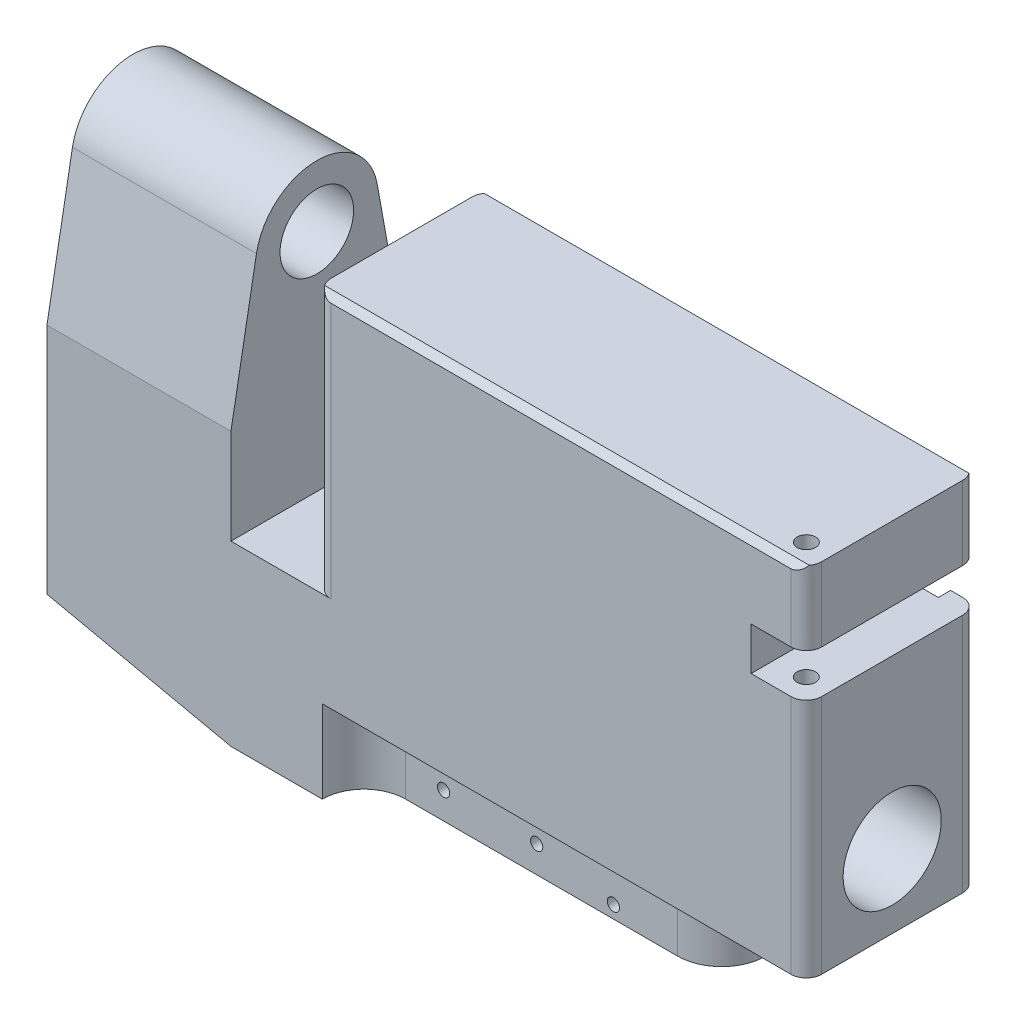
SolidWorks part; units mm, degrees
material "7050-T7651"
ref_plane "前视基准面" through (0, 0, 0) normal (0, 0, 1) x (1, 0, 0)
ref_plane "上视基准面" through (0, 0, 0) normal (0, 1, 0) x (1, 0, 0)
ref_plane "右视基准面" through (0, 0, 0) normal (1, 0, 0) x (0, 0, -1)
sketch "Sketch1" plane through (0, 0, 0) normal (0, 0, 1) x (1, 0, 0)
  line L0 (0, 0) -> (0, 46.74)
  line L1 (0, 46.74) -> (-30, 46.74)
  line L2 (-30, 46.74) -> (-30, -22.49)
  line L3 (-30, -22.49) -> (0, -28.98)
  line L4 (0, -28.98) -> (73.21, -28.98)
  line L5 (73.21, -28.98) -> (73.21, -15.51)
  line L6 (73.21, -15.51) -> (93.8, -15.51)
  line L7 (93.8, -15.51) -> (93.8, 23.71)
  line L8 (93.8, 23.71) -> (84.8, 23.71)
  line L9 (84.8, 23.71) -> (84.8, 30.71)
  line L10 (84.8, 30.71) -> (93.8, 30.71)
  line L11 (93.8, 30.71) -> (93.8, 42.75)
  line L12 (93.8, 42.75) -> (13.8, 42.75)
  line L13 (13.8, 42.75) -> (13.8, 0)
  line L14 (13.8, 0) -> (0, 0)
  circle A0 centre (55.55, -17.96) radius 1
  circle A1 centre (55.55, -26.93) radius 1
  circle A2 centre (43.04, -24.61) radius 1
  circle A3 centre (27.87, -24.61) radius 1
  dimension "D13" = 17.66
  dimension "D16" = 2
  dimension "D17" = 2
  dimension "D21" = 2
  dimension "D22" = 2
  dimension "D1" = 30
  dimension "D2" = 13.8
  dimension "D3" = 80
  dimension "D4" = 9
  dimension "D5" = 13.47
  dimension "D6" = 20.59
  dimension "D7" = 6.49
  dimension "D8" = 42.75
  dimension "D9" = 7
  dimension "D10" = 3.99
  dimension "D11" = 12.04
  dimension "D12" = 39.22
  dimension "D14" = 8.97
  dimension "D15" = 41.67
  dimension "D18" = 12.51
  dimension "D19" = 15.17
  dimension "D20" = 48.32
extrude "Extrude1" add sketch "Sketch1" along normal mid plane 28
chamfer "Chamfer1" distance 1 angle 45 2 edges at (53.8, 42.75, -14) (53.8, 42.75, 14)
fillet "Fillet1" radius 2.5 6 edges at (13.8, 20.875, -14) (93.8, 4.1, -14) (93.8, 36.23, -14) (93.8, 36.23, 14) (93.8, 4.1, 14) (13.8, 20.875, 14)
sketch "Sketch2" plane through (-30, 0, 0) normal (-1, 0, 0) x (0, 0, 1)
  line L0 (14, 46.74) -> (-14, 46.74) construction
  line L1 (-9.8404, 38.5197) -> (-14, 15.52)
  line L2 (-14, 46.74) -> (-14, -22.49) construction
  line L3 (0, 40.9581) -> (0, 6.2186) construction
  line L4 (9.8404, 38.5197) -> (14, 15.52)
  line L5 (-14, 15.52) -> (-14, 50.2525)
  line L6 (-14, 50.2525) -> (14, 50.2525)
  line L7 (14, 50.2525) -> (14, 15.52)
  arc A0 (9.8404, 38.5197) -> (-9.8404, 38.5197) centre (0, 36.74) ccw
  dimension "D1" = 31.22
  dimension "D2" = 10
extrude "Extrude4" cut sketch "Sketch2" against normal up to surface (30 mm away) up to face at (0, 23.37, 0)
sketch "Sketch3" plane through (0, 0, 0) normal (0, 0, 1) x (1, 0, 0)
  line L0 (85.68, 36.73) -> (-30, 36.73) construction
  line L1 (-30, 38.5197) -> (-30, 15.52) construction
  line L2 (-30, 36.73) -> (-30, 44.28)
  line L3 (-30, 46.74) -> (-30, 38.5197) construction
  line L4 (-30, 44.28) -> (-18.3, 44.28)
  line L5 (-18.3, 44.28) -> (-18.3, 42.73)
  line L6 (-18.3, 42.73) -> (0, 42.73)
  line L7 (0, 38.5197) -> (0, 46.74) construction
  line L8 (85.68, 36.73) -> (85.68, 41.245)
  line L9 (85.68, 41.245) -> (13.8, 41.245)
  line L10 (13.8, 0) -> (13.8, 42.75) construction
  line L11 (85.68, 36.73) -> (-30, 36.73)
  line L12 (0, 42.73) -> (0, 41.245)
  line L13 (13.8, 41.245) -> (0, 41.245)
  dimension "D1" = 9.03
  dimension "D2" = 12
  dimension "D3" = 15.1
  dimension "D4" = 11.7
  dimension "D5" = 71.88
  dimension "D6" = 59.22
revolve "Cut-Revolve1" cut sketch "Sketch3" angle 360 about L0
cosmetic thread "Cosmetic Thread1" parameters "D2"=16
sketch "Sketch4" plane through (0, 0, 0) normal (0, 0, 1) x (1, 0, 0)
  line L0 (-36.1569, -3.49) -> (100.5345, -3.49) construction
  line L2 (-32.9547, 6.51) -> (-32.9547, -3.49)
  line L4 (-32.9547, 6.51) -> (-1.1177, 6.51)
  line L5 (-1.1177, 6.51) -> (-1.1177, -0.99)
  line L6 (-1.1177, -0.99) -> (21.6, -0.99)
  line L7 (21.6, -0.99) -> (21.6, 4.51)
  line L8 (21.6, 4.51) -> (100.5345, 4.51)
  line L10 (100.5345, -3.49) -> (-32.9547, -3.49)
  line L13 (100.5345, 4.51) -> (100.5345, -3.49)
  dimension "D1" = 19
  dimension "D2" = 16
  dimension "D3" = 20
  dimension "D4" = 5
sketch "Sketch5" plane through (0, 42.75, 0) normal (0, 1, 0) x (1, 0, 0)
  line L0 (93.8, -11.5) -> (93.8, 11.5) construction
  line L2 (91.3, -14) -> (16.3, -14) construction
  circle A0 centre (89.8, -10) radius 1.5
  dimension "D1" = 4
  dimension "D3" = 3
  dimension "D2" = 4
extrude "Extrude5" cut sketch "Sketch5" against normal blind 23
sketch "Sketch6" plane through (0, 0, 0) normal (0, 1, 0) x (1, 0, 0)
  line L0 (93.8, -11.5) -> (93.8, 11.5) construction
  circle A0 centre (-13.6, 0) radius 2.55
  circle A1 centre (-24.9, 0) radius 2.05
  dimension "D1" = 107.4
  dimension "D3" = 5.1
  dimension "D4" = 4.1
  dimension "D2" = 118.7
extrude "Extrude6" cut sketch "Sketch6" against normal through all
cosmetic thread "Cosmetic Thread3" parameters "D2"=6
cosmetic thread "Cosmetic Thread4" parameters "D2"=5
sketch "Sketch7" plane through (0, -28.98, 0) normal (0, -1, 0) x (1, 0, 0)
  line L0 (-3.6205, 0) -> (80.3195, 0) construction
  line L1 (21.69, 7.2) -> (66.01, 7.2)
  line L2 (0, 14) -> (73.21, 14) construction
  line L3 (93.8, 11.5) -> (93.8, -11.5) construction
  line L4 (21.69, -7.2) -> (66.01, -7.2)
  line L5 (14.89, 14) -> (80.3195, 14)
  line L6 (73.21, 14) -> (91.3, 14) construction
  line L7 (80.3195, 14) -> (80.3195, -14)
  line L8 (73.21, -14) -> (91.3, -14) construction
  line L9 (80.3195, -14) -> (14.89, -14)
  arc A0 (66.01, 7.2) -> (66.01, -7.2) centre (66.01, 0) cw
  arc A1 (21.69, 7.2) -> (14.89, 14) centre (21.69, 14) cw
  arc A2 (21.69, -7.2) -> (14.89, -14) centre (21.69, -14) ccw
  dimension "D1" = 27.79
  dimension "D3" = 7.2
  dimension "D4" = 6.8
  dimension "D2" = 72.11
extrude "Extrude7" cut sketch "Sketch7" against normal up to surface (13.47 mm away) up to face at (86.2759, -15.51, 0)
sketch "Sketch8" plane through (0, -28.98, 0) normal (0, -1, 0) x (1, 0, 0)
  line L0 (21.69, 0) -> (66.01, 0) construction
  line L1 (21.69, 5.2) -> (66.01, 5.2)
  line L2 (21.69, -5.2) -> (66.01, -5.2)
  line L3 (93.8, 11.5) -> (93.8, -11.5) construction
  line L4 (21.69, 5.2) -> (21.69, -5.2)
  arc A1 (66.01, -5.2) -> (66.01, 5.2) centre (66.01, 0) ccw
  point P3 (43.85, 0)
  dimension "D1" = 5.2
  dimension "D2" = 27.79
  dimension "D3" = 72.11
  dimension "D4" = 10.4
extrude "Extrude8" cut sketch "Sketch8" against normal blind 15.49
sketch "Sketch9" plane through (0, -28.98, 0) normal (0, -1, 0) x (1, 0, 0)
  line L0 (17.74, 0) -> (21.69, 0) construction
  line L1 (21.69, 5.2) -> (21.69, -5.2) construction
  line L2 (17.74, 5.2) -> (21.69, 5.2)
  line L3 (17.74, -5.2) -> (21.69, -5.2)
  line L4 (93.8, 11.5) -> (93.8, -11.5) construction
  line L5 (11.7354, 5.4066) -> (15.0008, 2.4664) construction
  line L6 (11.7354, 5.4066) -> (17.74, 0) construction
  line L7 (0, 14) -> (14.89, 14) construction
  line L9 (13.2347, 7.0717) -> (15.7521, 4.805)
  line L10 (21.69, 5.2) -> (21.69, -5.2)
  line L11 (10.2361, 3.7414) -> (12.7535, 1.4747)
  arc A0 (12.7535, 1.4747) -> (17.74, -5.2) centre (17.74, 0) ccw
  arc A2 (13.2347, 7.0717) -> (10.2361, 3.7414) centre (11.7354, 5.4066) ccw
  arc A4 (17.74, 5.2) -> (15.7521, 4.805) centre (17.74, 0) ccw
  point P4 (19.715, 0)
  point P11 (13.3681, 3.9365)
  point P13 (13.9795, -3.386)
  dimension "D1" = 2.2407
  dimension "D3" = 5.2
  dimension "D2" = 76.06
  dimension "D4" = 42
extrude "Extrude21" cut sketch "Sketch9" against normal blind 10.11
sketch "Sketch22" plane through (0, -13.49, 0) normal (0, -1, 0) x (1, 0, 0)
  line L0 (93.8, 11.5) -> (93.8, -11.5) construction
  circle A0 centre (17.74, 0) radius 1.2
  dimension "D1" = 76.06
  dimension "D2" = 2.4
extrude "Extrude22" cut sketch "Sketch22" along normal through all
cosmetic thread "Cosmetic Thread11" parameters "D2"=3
sketch "Sketch23" plane through (0, -13.49, 0) normal (0, -1, 0) x (1, 0, 0)
  circle A0 centre (11.7354, 5.4066) radius 1.2
  dimension "D1" = 2.4
extrude "Extrude23" cut sketch "Sketch23" against normal blind 8 and the other way through all
cosmetic thread "Cosmetic Thread12" parameters "D2"=3
sketch "Sketch12" plane through (0, 0, 0) normal (0, 1, 0) x (1, 0, 0)
  line L1 (13.8, -11.5) -> (13.8, 11.5) construction
  line L2 (16.3, 14) -> (0, 14) construction
  circle A0 centre (9.63, 4.53) radius 1.5
  dimension "D1" = 9.47
  dimension "D3" = 3
  dimension "D2" = 4.17
extrude "Extrude12" cut sketch "Sketch12" against normal blind 8.5
sketch "Sketch13" plane through (0, -28.98, 0) normal (0, -1, 0) x (1, 0, 0)
  line L1 (93.8, 11.5) -> (93.8, -11.5) construction
  line L2 (0, -14) -> (14.89, -14) construction
  circle A0 centre (9.63, -4.53) radius 2.5
  dimension "D3" = 5
  dimension "D2" = 84.17
  dimension "9.4" = 9.47
extrude "Extrude13" cut sketch "Sketch13" against normal up to surface (20.48 mm away) up to face at (8.13, -8.5, -4.53)
cosmetic thread "Cosmetic Thread7" parameters "D1"=10, "D2"=6
sketch "Sketch14" plane through (0, 0, 0) normal (0, 1, 0) x (1, 0, 0)
  line L0 (-30, 9.8404) -> (-30, -9.8404) construction
  circle A0 centre (-13.6, 0) radius 2.25
  dimension "D1" = 16.4
  dimension "D2" = 4.5
extrude "Extrude14" cut sketch "Sketch14" along normal up to next
sketch "Sketch15" plane through (0, -13.49, 0) normal (0, -1, 0) x (1, 0, 0)
  line L0 (93.8, 11.5) -> (93.8, -11.5) construction
  line L1 (26.18, 2.5) -> (66.99, 2.5)
  line L2 (26.18, 2.5) -> (26.18, -2.5)
  line L3 (26.18, -2.5) -> (66.99, -2.5)
  line L4 (66.99, 2.5) -> (66.99, -2.5)
  line L5 (26.18, 2.5) -> (66.99, -2.5) construction
  line L6 (26.18, -2.5) -> (66.99, 2.5) construction
  point P0 (46.585, 0)
  dimension "D1" = 26.81
  dimension "D2" = 67.62
  dimension "D3" = 5
extrude "Extrude15" cut sketch "Sketch15" against normal blind 20
sketch "Sketch16" plane through (0, 0, 14) normal (0, 0, 1) x (1, 0, 0)
  line L0 (84.8, 30.71) -> (13.8, 30.71)
  line L1 (13.8, 0) -> (13.8, 42.75) construction
  line L2 (13.8, 30.71) -> (13.8, 6.5)
  line L3 (13.8, 6.5) -> (83.95, 6.5)
  line L4 (84.8, 23.71) -> (82.78, 23.71)
  line L5 (82.78, 23.71) -> (82.78, 19.71)
  line L6 (84.47, 18.02) -> (85.26, 18.02)
  line L7 (87.32, 15.96) -> (87.32, 9.87)
  line L8 (93.8, 23.71) -> (93.8, -15.51) construction
  line L9 (91.3, 23.71) -> (84.8, 23.71) construction
  line L10 (84.8, 30.71) -> (84.8, 23.71)
  arc A0 (87.32, 9.87) -> (83.95, 6.5) centre (83.95, 9.87) cw
  arc A1 (82.78, 19.71) -> (84.47, 18.02) centre (84.47, 19.71) ccw
  arc A2 (85.26, 18.02) -> (87.32, 15.96) centre (85.26, 15.96) cw
  dimension "D3" = 3.37
  dimension "D5" = 8.54
  dimension "D4" = 9.33
  dimension "D1" = 24.21
  dimension "D2" = 11.02
  dimension "D7" = 4
  dimension "D8" = 7.75
sketch "Sketch24" plane through (0, 0, -14) normal (0, 0, -1) x (-1, 0, 0)
  line L0 (-84.8, 30.71) -> (-13.8, 30.71)
  line L1 (-13.8, 30.71) -> (-13.8, 6.5)
  line L2 (-84.8, 30.71) -> (-84.8, 23.71)
  line L3 (-84.8, 23.71) -> (-82.78, 23.71)
  line L4 (-82.78, 23.71) -> (-82.78, 19.71)
  line L5 (-87.32, 15.96) -> (-87.32, 9.87)
  line L8 (-82.78, 23.71) -> (-82.78, 19.71)
  line L9 (-84.8, 23.71) -> (-82.78, 23.71)
  line L10 (-84.8, 30.71) -> (-84.8, 23.71)
  line L11 (-13.8, 30.71) -> (-84.8, 30.71)
  line L12 (-13.8, 6.5) -> (-13.8, 30.71)
  line L13 (-83.95, 6.5) -> (-13.8, 6.5)
  line L14 (-87.32, 15.96) -> (-87.32, 9.87)
  line L15 (-84.47, 18.02) -> (-85.26, 18.02)
  line L21 (-83.95, 6.5) -> (-13.8, 6.5)
  line L23 (-84.47, 18.02) -> (-85.26, 18.02)
  arc A0 (-87.32, 9.87) -> (-83.95, 6.5) centre (-83.95, 9.87) ccw
  arc A1 (-85.26, 18.02) -> (-87.32, 15.96) centre (-85.26, 15.96) ccw
  arc A2 (-82.78, 19.71) -> (-84.47, 18.02) centre (-84.47, 19.71) cw
  arc A3 (-87.32, 9.87) -> (-83.95, 6.5) centre (-83.95, 9.87) ccw
  arc A4 (-85.26, 18.02) -> (-87.32, 15.96) centre (-85.26, 15.96) ccw
  arc A5 (-84.47, 18.02) -> (-82.78, 19.71) centre (-84.47, 19.71) ccw
  dimension "D8" = 70.15
  dimension "D10" = 2.06
  dimension "D11" = 1.69
  dimension "D1" = 0
extrude "Extrude24" cut sketch "Sketch24" against normal blind 19
sketch "Sketch17" plane through (0, 0, 14) normal (0, 0, 1) x (1, 0, 0)
  line L0 (84.8, 30.71) -> (91.3, 30.71) construction
  line L1 (17.8, 32.71) -> (50.14, 32.71)
  line L2 (15.8, 30.71) -> (15.8, 28.71)
  line L3 (15.8, 28.71) -> (52.14, 28.71)
  line L4 (52.14, 30.71) -> (52.14, 28.71)
  line L5 (15.8, 32.71) -> (52.14, 28.71) construction
  line L6 (15.8, 28.71) -> (52.14, 32.71) construction
  line L7 (15.8, 23.71) -> (15.8, 6.5)
  line L8 (83.95, 6.5) -> (16.3, 6.5) construction
  line L9 (17.8, 4.5) -> (87.32, 4.5)
  line L10 (89.32, 6.5) -> (89.32, 23.71)
  line L11 (91.3, 23.71) -> (84.8, 23.71) construction
  line L12 (89.32, 23.71) -> (15.8, 23.71)
  line L13 (93.8, -15.51) -> (93.8, 23.71) construction
  line L17 (13.8, 6.5) -> (13.8, 30.71) construction
  arc A0 (15.8, 6.5) -> (17.8, 4.5) centre (17.8, 6.5) ccw
  arc A1 (87.32, 4.5) -> (89.32, 6.5) centre (87.32, 6.5) ccw
  arc A2 (17.8, 32.71) -> (15.8, 30.71) centre (17.8, 30.71) ccw
  arc A3 (50.14, 32.71) -> (52.14, 30.71) centre (50.14, 30.71) cw
  point P0 (33.97, 30.71)
  dimension "D6" = 2
  dimension "D1" = 4.48
  dimension "D3" = 2
  dimension "D4" = 2
  dimension "D5" = 36.34
  dimension "D7" = 2
sketch "Sketch25" plane through (0, 0, -14) normal (0, 0, -1) x (-1, 0, 0)
  line L4 (-15.8, 6.5) -> (-15.8, 23.71)
  line L5 (-87.32, 4.5) -> (-17.8, 4.5)
  line L6 (-89.32, 23.71) -> (-89.32, 6.5)
  line L7 (-15.8, 23.71) -> (-89.32, 23.71)
  line L8 (-15.8, 6.5) -> (-15.8, 23.71)
  line L9 (-87.32, 4.5) -> (-17.8, 4.5)
  line L10 (-89.32, 23.71) -> (-89.32, 6.5)
  line L11 (-15.8, 23.71) -> (-89.32, 23.71)
  line L12 (-17.8, 32.71) -> (-50.14, 32.71)
  line L13 (-52.14, 30.71) -> (-52.14, 28.71)
  line L14 (-52.14, 28.71) -> (-15.8, 28.71)
  line L15 (-15.8, 28.71) -> (-15.8, 30.71)
  line L16 (-17.8, 32.71) -> (-50.14, 32.71)
  line L17 (-52.14, 30.71) -> (-52.14, 28.71)
  line L18 (-52.14, 28.71) -> (-15.8, 28.71)
  line L19 (-15.8, 28.71) -> (-15.8, 30.71)
  arc A2 (-17.8, 4.5) -> (-15.8, 6.5) centre (-17.8, 6.5) ccw
  arc A3 (-89.32, 6.5) -> (-87.32, 4.5) centre (-87.32, 6.5) ccw
  arc A4 (-17.8, 4.5) -> (-15.8, 6.5) centre (-17.8, 6.5) ccw
  arc A5 (-89.32, 6.5) -> (-87.32, 4.5) centre (-87.32, 6.5) ccw
  arc A6 (-50.14, 32.71) -> (-52.14, 30.71) centre (-50.14, 30.71) ccw
  arc A7 (-15.8, 30.71) -> (-17.8, 32.71) centre (-17.8, 30.71) ccw
  arc A8 (-50.14, 32.71) -> (-52.14, 30.71) centre (-50.14, 30.71) ccw
  arc A9 (-15.8, 30.71) -> (-17.8, 32.71) centre (-17.8, 30.71) ccw
  dimension "D1" = 0
  dimension "D2" = 0
extrude "Extrude25" cut sketch "Sketch25" against normal blind 2
sketch "Sketch18" plane through (0, 0, 5) normal (0, 0, 1) x (1, 0, 0)
  line L0 (38.25, 27.21) -> (68.47, 27.21) construction
  line L1 (38.25, 30.71) -> (68.47, 30.71)
  line L2 (38.25, 23.71) -> (68.47, 23.71)
  line L4 (93.8, 23.71) -> (93.8, -15.51) construction
  line L5 (14.3, 42.75) -> (93.3, 42.75) construction
  line L22 (14.89, -28.98) -> (14.89, -15.51)
  line L23 (14.89, -15.51) -> (91.3, -15.51)
  line L24 (91.3, -15.51) -> (91.3, 23.71)
  line L25 (91.3, 23.71) -> (84.8, 23.71)
  line L26 (84.8, 23.71) -> (84.8, 30.71)
  line L27 (84.8, 30.71) -> (91.3, 30.71)
  line L28 (91.3, 30.71) -> (91.3, 41.75)
  line L29 (91.3, 41.75) -> (16.3, 41.75)
  line L30 (16.3, 41.75) -> (16.3, 0)
  line L31 (16.3, 0) -> (0, 0)
  line L32 (0, 0) -> (0, 15.52)
  line L33 (0, 15.52) -> (-30, 15.52)
  line L34 (-30, 15.52) -> (-30, -22.49)
  line L35 (-30, -22.49) -> (0, -28.98)
  line L36 (0, -28.98) -> (14.89, -28.98)
  line L37 (14.89, -28.98) -> (14.89, -15.51)
  line L38 (14.89, -15.51) -> (91.3, -15.51)
  line L39 (91.3, -15.51) -> (91.3, 23.71)
  line L40 (91.3, 23.71) -> (84.8, 23.71)
  line L41 (84.8, 23.71) -> (84.8, 30.71)
  line L42 (84.8, 30.71) -> (91.3, 30.71)
  line L43 (91.3, 30.71) -> (91.3, 41.75)
  line L44 (91.3, 41.75) -> (16.3, 41.75)
  line L45 (16.3, 41.75) -> (16.3, 0)
  line L46 (16.3, 0) -> (0, 0)
  line L47 (0, 0) -> (0, 15.52)
  line L48 (0, 15.52) -> (-30, 15.52)
  line L49 (-30, 15.52) -> (-30, -22.49)
  line L50 (-30, -22.49) -> (0, -28.98)
  line L51 (0, -28.98) -> (14.89, -28.98)
  arc A0 (38.25, 30.71) -> (38.25, 23.71) centre (38.25, 27.21) ccw
  arc A1 (68.47, 23.71) -> (68.47, 30.71) centre (68.47, 27.21) ccw
  point P2 (53.36, 27.21)
  dimension "D1" = 3.5
  dimension "D2" = 30.22
  dimension "D3" = 25.33
  dimension "D4" = 15.54
  dimension "D5" = 0
sketch "Sketch19" [suppressed] plane through (0, 0, 5) normal (0, 0, 1) x (1, 0, 0)
  line L0 (14.3, 42.75) -> (93.3, 42.75) construction
  line L1 (93.8, 23.71) -> (93.8, -15.51) construction
  line L3 (82.78, 23.71) -> (89.32, 23.71) construction
  circle A0 centre (42.01, 11.33) radius 1.25
  circle A1 centre (85.26, 15.96) radius 1
  circle A2 centre (21.56, 26.46) radius 1.1
  circle A3 centre (65.64, 11.33) radius 1.25
  dimension "D1" = 31.42
  dimension "D2" = 2.5
  dimension "D7" = 2
  dimension "D10" = 2.2
  dimension "D3" = 51.79
  dimension "D5" = 8.54
  dimension "D6" = 7.75
  dimension "D8" = 16.29
  dimension "D9" = 20.45
  dimension "D4" = 2
sketch "Sketch26" plane through (0, 0, 5) normal (0, 0, -1) x (-1, 0, 0)
  line L2 (-38.25, 30.71) -> (-68.47, 30.71)
  line L3 (-68.47, 23.71) -> (-38.25, 23.71)
  line L4 (-38.25, 30.71) -> (-68.47, 30.71)
  line L5 (-68.47, 23.71) -> (-38.25, 23.71)
  arc A2 (-68.47, 30.71) -> (-68.47, 23.71) centre (-68.47, 27.21) ccw
  arc A3 (-38.25, 23.71) -> (-38.25, 30.71) centre (-38.25, 27.21) ccw
  arc A4 (-68.47, 30.71) -> (-68.47, 23.71) centre (-68.47, 27.21) ccw
  arc A5 (-38.25, 23.71) -> (-38.25, 30.71) centre (-38.25, 27.21) ccw
  dimension "D1" = 0
extrude "Extrude26" cut sketch "Sketch26" against normal blind 5
revolve "Cut-Revolve2" cut sketch "Sketch4" angle 360 about L0
cosmetic thread "Cosmetic Thread8" parameters "D1"=20, "D2"=18
sketch "Sketch27" plane through (0, 0, 5) normal (0, 0, -1) x (-1, 0, 0)
  circle A1 centre (-65.64, 11.33) radius 1.25
  circle A2 centre (-65.64, 11.33) radius 1.25
  circle A3 centre (-21.56, 26.46) radius 1.1
  circle A4 centre (-21.56, 26.46) radius 1.1
  circle A5 centre (-85.26, 15.96) radius 1
  circle A6 centre (-85.26, 15.96) radius 1
  circle A7 centre (-42.01, 11.33) radius 1.25
  circle A8 centre (-42.01, 11.33) radius 1.25
  dimension "D1" = 0
  dimension "D2" = 0
  dimension "D3" = 0
  dimension "D4" = 0
extrude "Extrude27" cut sketch "Sketch27" against normal blind 6
sketch "Sketch20" plane through (0, 0, -12) normal (0, 0, 1) x (1, 0, 0)
  line L1 (93.8, 23.71) -> (93.8, -15.51) construction
  line L2 (91.3, 23.71) -> (84.8, 23.71) construction
  circle A0 centre (84.47, 19.71) radius 0.6
  dimension "D1" = 1.2
  dimension "D3" = 9.33
  dimension "D4" = 4
extrude "Extrude20" cut sketch "Sketch20" along normal blind 8
cosmetic thread "Cosmetic Thread10" parameters "D2"=2
sketch "草图1" plane through (0, 30.71, 0) normal (0, -1, 0) x (1, 0, 0)
  line L0 (93.8, 11.5) -> (93.8, -11.5) construction
  line L1 (36.05, 2.26) -> (79.02, 2.26)
  line L2 (36.05, 2.26) -> (36.05, -2.26)
  line L3 (36.05, -2.26) -> (79.02, -2.26)
  line L4 (79.02, 2.26) -> (79.02, -2.26)
  line L5 (36.05, 2.26) -> (79.02, -2.26) construction
  line L6 (36.05, -2.26) -> (79.02, 2.26) construction
  point P0 (57.535, 0)
  dimension "D1" = 14.78
  dimension "D2" = 4.52
  dimension "D3" = 42.97
extrude "切除-拉伸1" cut sketch "草图1" against normal up to next
